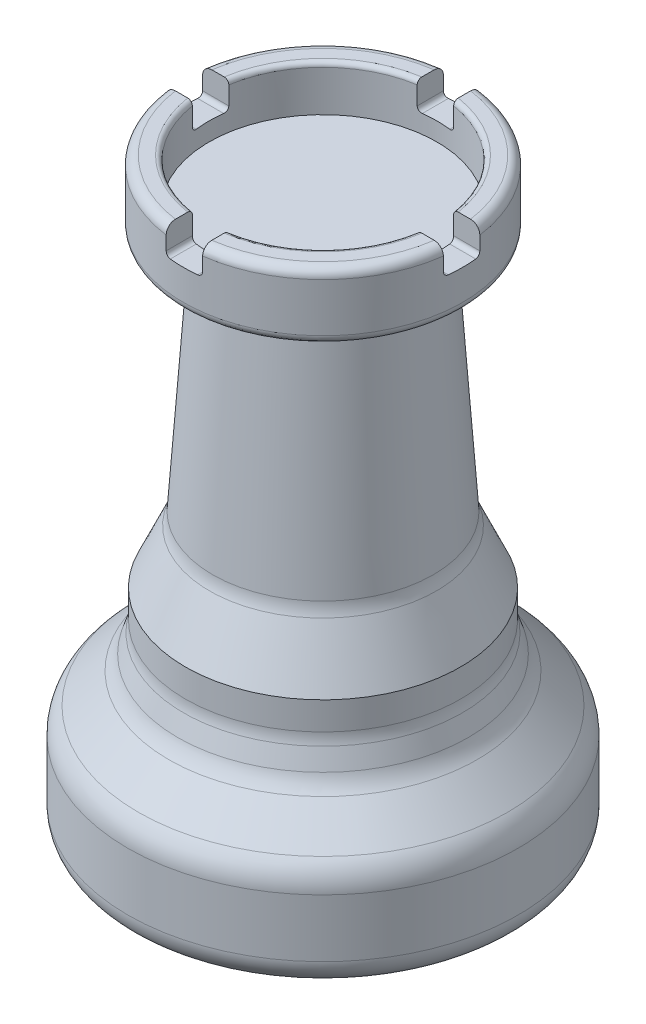
SolidWorks part; units mm, degrees
ref_plane "Front Plane" through (0, 0, 0) normal (0, 0, 1) x (1, 0, 0)
ref_plane "Top Plane" through (0, 0, 0) normal (0, 1, 0) x (1, 0, 0)
ref_plane "Right Plane" through (0, 0, 0) normal (1, 0, 0) x (0, 0, -1)
sketch "Sketch1" plane through (0, 0, 0) normal (0, 0, 1) x (1, 0, 0)
  line L0 (31.1667, 136.5) -> (155.8333, 136.5) construction
sketch "Sketch2" plane through (0, 0, 0) normal (0, 0, 1) x (1, 0, 0)
  line L0 (0, 0) -> (45, 0) construction
  line L1 (22.5, 0) -> (22.5, 46.9776) construction
  line L2 (1.0727, 3) -> (1.0727, 5.4666)
  line L3 (1.0727, 5.4666) -> (1.0727, 9.3429)
  line L4 (2.2443, 12.1713) -> (5.5794, 15.5064)
  line L5 (6.5607, 17.116) -> (7.2076, 19.1378)
  line L6 (7.3978, 20.3567) -> (7.3978, 23.4093)
  line L7 (7.3978, 23.4093) -> (10.0487, 29.3083)
  line L8 (10.391, 30.6768) -> (12.0067, 54.4641)
  line L9 (11.6022, 55.3369) -> (10.8737, 55.8737)
  line L10 (10.8737, 55.8737) -> (10.8737, 57.1816)
  line L11 (10.8737, 57.1816) -> (8.1621, 57.1816)
  line L12 (4.0727, 0) -> (22.5, 0)
  line L13 (22.5, 0) -> (22.5, 64.5151)
  line L14 (7.1621, 58.1816) -> (7.1621, 63.5151)
  line L15 (8.1621, 64.5151) -> (22.5, 64.5151)
  arc A0 (7.1621, 63.5151) -> (8.1621, 64.5151) centre (8.1621, 63.5151) cw
  arc A1 (8.1621, 57.1816) -> (7.1621, 58.1816) centre (8.1621, 58.1816) cw
  arc A2 (12.0067, 54.4641) -> (11.6022, 55.3369) centre (11.0089, 54.5319) ccw
  arc A3 (10.391, 30.6768) -> (10.0487, 29.3083) centre (6.4002, 30.9479) cw
  arc A4 (4.0727, 0) -> (1.0727, 3) centre (4.0727, 3) cw
  arc A5 (7.3978, 20.3567) -> (7.2076, 19.1378) centre (3.3978, 20.3567) cw
  arc A6 (6.5607, 17.116) -> (5.5794, 15.5064) centre (2.751, 18.3349) cw
  arc A7 (1.0727, 9.3429) -> (2.2443, 12.1713) centre (5.0727, 9.3429) cw
  point P26 (1.0727, 0)
  dimension "D2" = 1
  dimension "D3" = 1
  dimension "D4" = 1
  dimension "D5" = 4
  dimension "D6" = 3
  dimension "D7" = 4
  dimension "D8" = 4
  dimension "D9" = 4
  dimension "D1" = 45
revolve "Revolve1" add sketch "Sketch2" angle 360 about L13
sketch "Sketch3" plane through (0, 64.5151, 0) normal (0, 1, 0) x (1, 0, 0)
  circle A0 centre (22.5, 0) radius 12.5
  dimension "D1" = 25
extrude "Cut-Extrude1" cut sketch "Sketch3" against normal blind 5
sketch "Sketch4" plane through (0, 64.5151, 0) normal (0, 1, 0) x (1, 0, 0)
  line L0 (20.5, -2) -> (4.5249, -2)
  line L1 (40.4751, 2) -> (24.5, 2)
  line L2 (40.4751, 2) -> (40.4751, -2)
  line L3 (40.4751, -2) -> (24.5, -2)
  line L4 (4.5249, 2) -> (4.5249, -2)
  line L5 (40.4751, 2) -> (4.5249, -2) construction
  line L6 (40.4751, -2) -> (4.5249, 2) construction
  line L7 (24.5, 18.5652) -> (20.5, 18.5652)
  line L8 (24.5, 18.5652) -> (24.5, 2)
  line L9 (24.5, -18.5652) -> (20.5, -18.5652)
  line L10 (20.5, 18.5652) -> (20.5, 2)
  line L11 (24.5, 18.5652) -> (20.5, -18.5652) construction
  line L12 (24.5, -18.5652) -> (20.5, 18.5652) construction
  line L13 (24.5, -2) -> (24.5, -18.5652)
  line L14 (20.5, -2) -> (20.5, -18.5652)
  line L15 (20.5, 2) -> (4.5249, 2)
  point P0 (22.5, 0)
  point P6 (22.5, 0)
  dimension "D1" = 4
  dimension "D2" = 4
extrude "Cut-Extrude2" cut sketch "Sketch4" against normal blind 3
fillet "Fillet1" radius 0.5 8 edges at (8.727, 61.5151, -2) (20.5, 61.5151, -13.773) (20.5, 61.5151, 13.773) (8.727, 61.5151, 2) (24.5, 61.5151, -13.773) (24.5, 61.5151, 13.773) (36.273, 61.5151, -2) (36.273, 61.5151, 2)
fillet "Fillet2" radius 0.5 4 edges at (13.6612, 64.5151, 8.8388) (13.6612, 64.5151, -8.8388) (31.3388, 64.5151, -8.8388) (31.3388, 64.5151, 8.8388)
